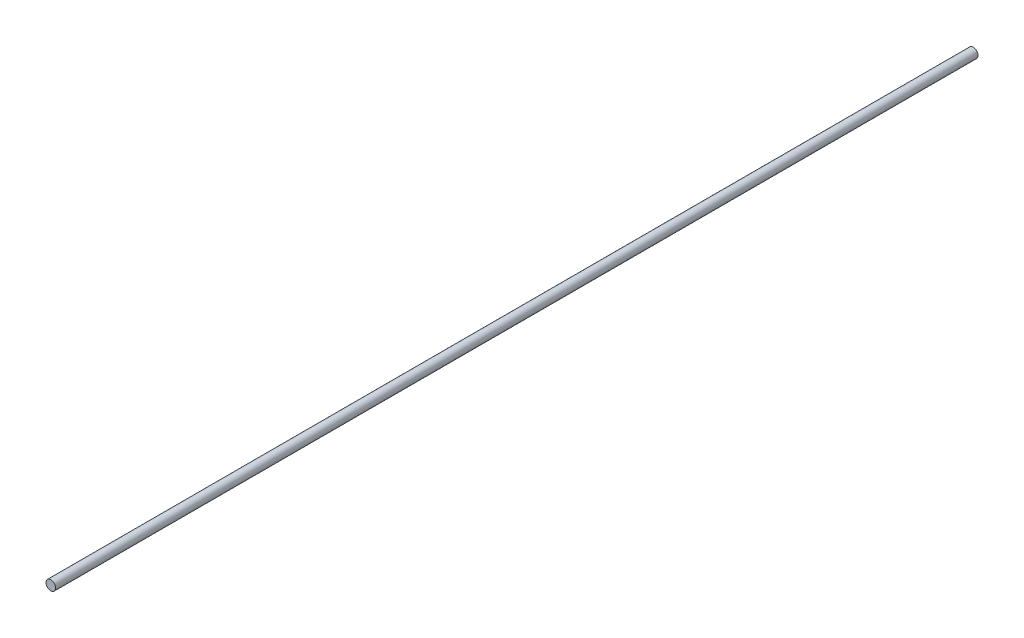
SolidWorks part; units mm, degrees
ref_plane "Front Plane" through (0, 0, 0) normal (0, 0, 1) x (1, 0, 0)
ref_plane "Top Plane" through (0, 0, 0) normal (0, 1, 0) x (1, 0, 0)
ref_plane "Right Plane" through (0, 0, 0) normal (1, 0, 0) x (0, 0, -1)
sketch "Sketch1" plane through (0, 0, 0) normal (0, 0, 1) x (1, 0, 0)
  circle A0 centre (0, 0) radius 4.7625
  dimension "D1" = 9.525
extrude "Boss-Extrude1" add sketch "Sketch1" along normal mid plane 914.4
